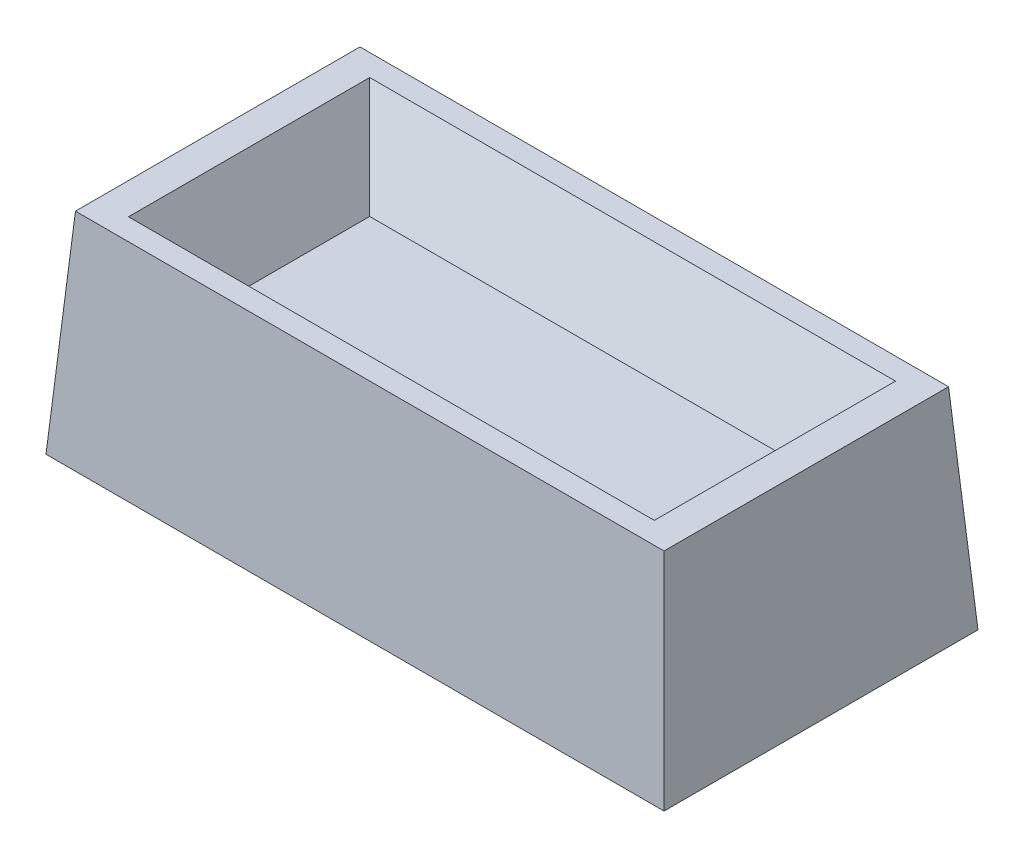
SolidWorks part; units mm, degrees
ref_plane "Front Plane" through (0, 0, 0) normal (0, 0, 1) x (1, 0, 0)
ref_plane "Top Plane" through (0, 0, 0) normal (0, 1, 0) x (1, 0, 0)
ref_plane "Right Plane" through (0, 0, 0) normal (1, 0, 0) x (0, 0, -1)
sketch "Sketch1" plane through (0, 0, 0) normal (0, 1, 0) x (1, 0, 0)
  line L1 (-102.8928, -52.2674) -> (102.8928, -52.2674)
  line L2 (-102.8928, -52.2674) -> (-102.8928, 52.2674)
  line L3 (-102.8928, 52.2674) -> (102.8928, 52.2674)
  line L4 (102.8928, -52.2674) -> (102.8928, 52.2674)
  line L5 (-102.8928, -52.2674) -> (102.8928, 52.2674) construction
  line L6 (-102.8928, 52.2674) -> (102.8928, -52.2674) construction
  point P0 (0, 0)
extrude "Boss-Extrude1" add sketch "Sketch1" along normal blind 70.104 draft 4
sketch "Sketch2" plane through (0, 70.104, 0) normal (0, 1, 0) x (1, 0, 0)
  line L1 (-72.8794, -25.487) -> (72.8794, -25.487)
  line L2 (-72.8794, -25.487) -> (-72.8794, 25.487)
  line L3 (-72.8794, 25.487) -> (72.8794, 25.487)
  line L4 (72.8794, -25.487) -> (72.8794, 25.487)
  line L5 (-72.8794, -25.487) -> (72.8794, 25.487) construction
  line L6 (-72.8794, 25.487) -> (72.8794, -25.487) construction
  point P0 (0, 0)
extrude "Cut-Extrude1" cut sketch "Sketch2" against normal blind 25.4
draft "Draft1" type of draft neutral plane draft angle 30 faces to draft 4 face at (0, 57.404, 25.487) face at (72.8794, 57.404, 0) face at (0, 57.404, -25.487) face at (-72.8794, 57.404, 0) neutral plane through (0, 44.704, 0) neutral plane normal (0, 1, 0) parameters "D1"=30
shell "Shell1" thickness 1.5875
